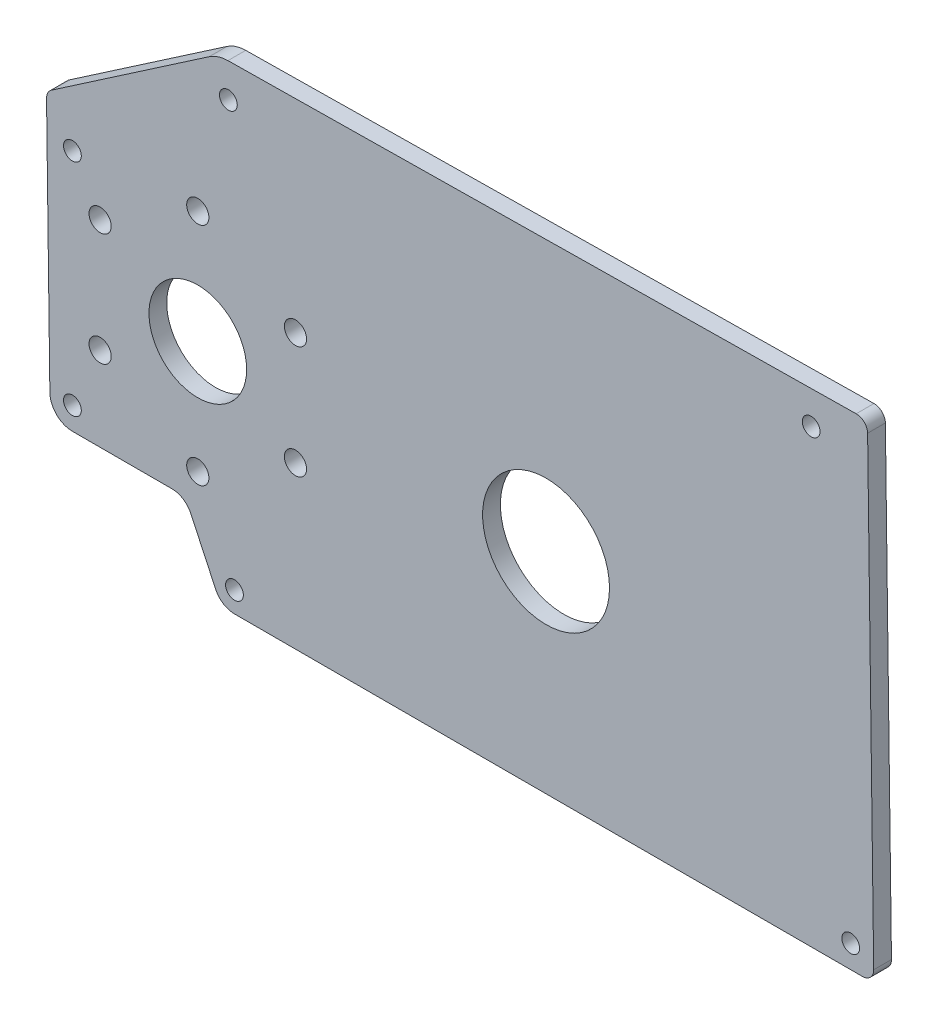
SolidWorks part; units mm, degrees
ref_plane "Front Plane" through (0, 0, 0) normal (0, 0, 1) x (1, 0, 0)
ref_plane "Top Plane" through (0, 0, 0) normal (0, 1, 0) x (1, 0, 0)
ref_plane "Right Plane" through (0, 0, 0) normal (1, 0, 0) x (0, 0, -1)
sketch "Sketch1" plane through (0, 0, 0) normal (0, 0, 1) x (1, 0, 0)
  line L15 (16.7683, 33.6255) -> (39.2181, 33.6255) construction
  line L35 (17.5661, -48.5742) -> (-4.8581, -48.5742)
  line L73 (21.8007, -51.2691) -> (27.3987, -63.2442)
  line L74 (31.6333, -65.9391) -> (66.5236, -65.9391)
  line L77 (66.5236, -65.9391) -> (173.0612, -65.9391)
  line L81 (-4.8581, -43.4942) -> (-4.8581, 16.476) construction
  line L84 (30.1658, 41.2448) -> (171.6576, 43.1095)
  line L86 (174.2308, 40.6031) -> (175.601, -63.3656)
  line L88 (39.2181, 33.6255) -> (62.4224, 33.6255) construction
  line L89 (16.7683, 33.6255) -> (25.9645, 39.9151)
  line L90 (-6.6198, 17.6295) -> (-9.583, 15.6029)
  line L91 (-10.6888, 13.4729) -> (-9.9381, -43.4942)
  line L92 (-6.6198, 17.6295) -> (16.7683, 33.6255)
  line L96 (23.3772, -16.9102) -> (23.3772, -42.3102) construction
  circle A32 centre (-4.8581, -43.4942) radius 2
  circle A46 centre (101.8113, -18.6491) radius 14.29
  circle A47 centre (31.6333, -61.2647) radius 2
  circle A52 centre (30.2662, 33.6255) radius 2
  arc A57 (31.6333, -65.9391) -> (27.3987, -63.2442) centre (31.6333, -61.2647) cw
  arc A58 (21.8007, -51.2691) -> (17.5661, -48.5742) centre (17.5661, -53.2487) ccw
  circle A59 centre (170.4264, -60.7758) radius 2
  circle A60 centre (161.5139, 35.5525) radius 2
  arc A66 (173.0612, -65.9391) -> (175.601, -63.3656) centre (173.0612, -63.3991) ccw
  arc A67 (174.2308, 40.6031) -> (171.6576, 43.1095) centre (171.6911, 40.5697) ccw
  arc A69 (-4.8581, -48.5742) -> (-9.9381, -43.4942) centre (-4.8581, -43.4942) cw
  circle A70 centre (-4.8581, 6.1453) radius 2
  arc A72 (30.1658, 41.2448) -> (25.9645, 39.9151) centre (30.2662, 33.6255) ccw
  circle A76 centre (23.3772, -42.3102) radius 2.5
  arc A80 (-10.6888, 13.4729) -> (-9.583, 15.6029) centre (-8.1491, 13.5063) cw
  circle A81 centre (23.3772, -16.9102) radius 11
  circle A82 centre (1.3802, -29.6102) radius 2.5
  circle A83 centre (1.3802, -4.2102) radius 2.5
  circle A84 centre (23.3772, 8.4898) radius 2.5
  circle A85 centre (45.3743, -4.2102) radius 2.5
  circle A86 centre (45.3743, -29.6102) radius 2.5
  point P0 (0, 0)
  point P35 (103.8286, -4.5315)
  point P54 (23.3772, -16.9102)
  point P58 (23.3772, -16.9102)
  dimension "D1" = 4
  dimension "D2" = 5.08
  dimension "D3" = 2.54
  dimension "D4" = 2.54
  dimension "D5" = 28.58
  dimension "D6" = 4
  dimension "D7" = 6
  dimension "D8" = 5
  dimension "D10" = 22
  dimension "D9" = 25.4
extrude "Boss-Extrude1" add sketch "Sketch1" along normal blind 4
